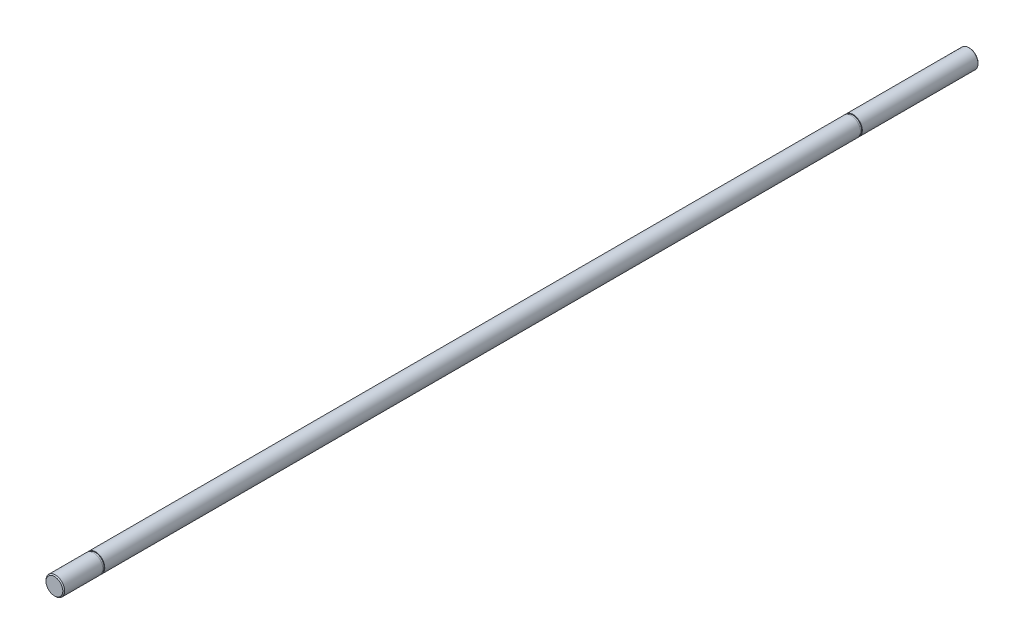
SolidWorks part; units mm, degrees
ref_plane "前视基准面" through (0, 0, 0) normal (0, 0, 1) x (1, 0, 0)
ref_plane "上视基准面" through (0, 0, 0) normal (0, 1, 0) x (1, 0, 0)
ref_plane "右视基准面" through (0, 0, 0) normal (1, 0, 0) x (0, 0, -1)
sketch "草图1" plane through (0, 0, 0) normal (0, 0, 1) x (1, 0, 0)
  circle A0 centre (0, 0) radius 5
  dimension "D1" = 10
extrude "拉伸1" add sketch "草图1" along normal blind 532
sketch "草图2" plane through (0, 0, 0) normal (0, 1, 0) x (1, 0, 0)
  line L0 (-12.5, -62.5) -> (12.5, -62.5) construction
  line L1 (-5, 0) -> (-5, -532) construction
  line L5 (12.5, -469.5) -> (-12.5, -469.5) construction
  line L10 (-8.082, -469.5) -> (-4.65, -469.5)
  line L11 (-9.2826, -62.5) -> (-4.65, -62.5)
  line L12 (-9.2826, -62.5) -> (-9.2826, -63.5)
  line L13 (-9.2826, -63.5) -> (-4.65, -63.5)
  line L14 (-4.65, -62.5) -> (-4.65, -63.5)
  line L15 (-8.082, -469.5) -> (-8.082, -468.5)
  line L16 (-8.082, -468.5) -> (-4.65, -468.5)
  line L17 (-4.65, -469.5) -> (-4.65, -468.5)
  dimension "D1" = 1
  dimension "D2" = 1
  dimension "D3" = 0.35
  dimension "D4" = 0.35
revolve "切除-旋转2" cut sketch "草图2" angle 360 about axis through (0, 0, 532) along (0, 0, -1)
chamfer "倒角1" distance 0.5 angle 45 1 edges at (5, 0, 0)
sketch "草图3" plane through (0, 0, 0) normal (0, 1, 0) x (1, 0, 0)
  line L0 (-7.5, -488.5) -> (7.5, -488.5) construction
  line L1 (-11.9106, -490.5) -> (26.7866, -490.5)
  line L2 (-11.9106, -490.5) -> (-11.9106, -549.702)
  line L3 (-11.9106, -549.702) -> (26.7866, -549.702)
  line L4 (26.7866, -490.5) -> (26.7866, -549.702)
  dimension "D1" = 2
extrude "切除-拉伸1" cut sketch "草图3" against normal mid plane 20
chamfer "倒角2" distance 0.5 angle 45 1 edges at (-5, 0, 490.5)
